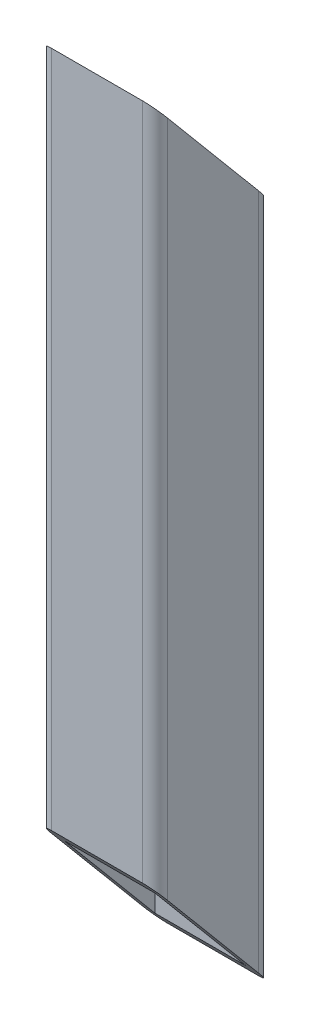
SolidWorks part; units mm, degrees
material "Plain Carbon Steel"
ref_plane "Front Plane" through (0, 0, 0) normal (0, 0, 1) x (1, 0, 0)
ref_plane "Top Plane" through (0, 0, 0) normal (0, 1, 0) x (1, 0, 0)
ref_plane "Right Plane" through (0, 0, 0) normal (1, 0, 0) x (0, 0, -1)
sketch "Sketch1" plane through (0, 0, 0) normal (0, 1, 0) x (1, 0, 0)
  line L1 (2.8, 0) -> (22.8, 0)
  line L2 (0, -2.8) -> (0, -22.8)
  line L3 (2.8, -25.6) -> (22.8, -25.6)
  line L4 (25.6, -2.8) -> (25.6, -22.8)
  arc A0 (22.8, 0) -> (25.6, -2.8) centre (22.8, -2.8) cw
  arc A1 (22.8, -25.6) -> (25.6, -22.8) centre (22.8, -22.8) ccw
  arc A2 (0, -22.8) -> (2.8, -25.6) centre (2.8, -22.8) ccw
  arc A3 (2.8, 0) -> (0, -2.8) centre (2.8, -2.8) ccw
  point P7 (25.6, 0)
  point P10 (25.6, -25.6)
  point P15 (0, 0)
  dimension "D2" = 2.8
  dimension "D1" = 25.6
extrude "Boss-Extrude1" add sketch "Sketch1" along normal blind 180
sketch "Sketch3" plane through (0, 0, 0) normal (0, -1, 0) x (-1, 0, 0)
  line L4 (-2.8, -2.8) -> (-22.8, -2.8)
  line L5 (-2.8, -2.8) -> (-2.8, -22.8)
  line L6 (-2.8, -22.8) -> (-22.8, -22.8)
  line L7 (-22.8, -2.8) -> (-22.8, -22.8)
  line L8 (-2.8, -2.8) -> (-22.8, -22.8) construction
  line L9 (-2.8, -22.8) -> (-22.8, -2.8) construction
  point P6 (-12.8, -12.8)
extrude "Cut-Extrude1" cut sketch "Sketch3" against normal blind 1040.5
sketch "Sketch4" plane through (0, 0, 0) normal (1, 0, 0) x (0, 0, -1)
  line L1 (0, 0) -> (-37.642, 44.86)
extrude "Cut-Extrude5" cut sketch "Sketch4" against normal through all and the other way through all
sketch "Sketch5" plane through (0, 0, 0) normal (1, 0, 0) x (0, 0, -1)
  line L0 (-25.6, 180) -> (12.0114, 135.1578)
extrude "Cut-Extrude6" cut sketch "Sketch5" against normal through all and the other way through all
